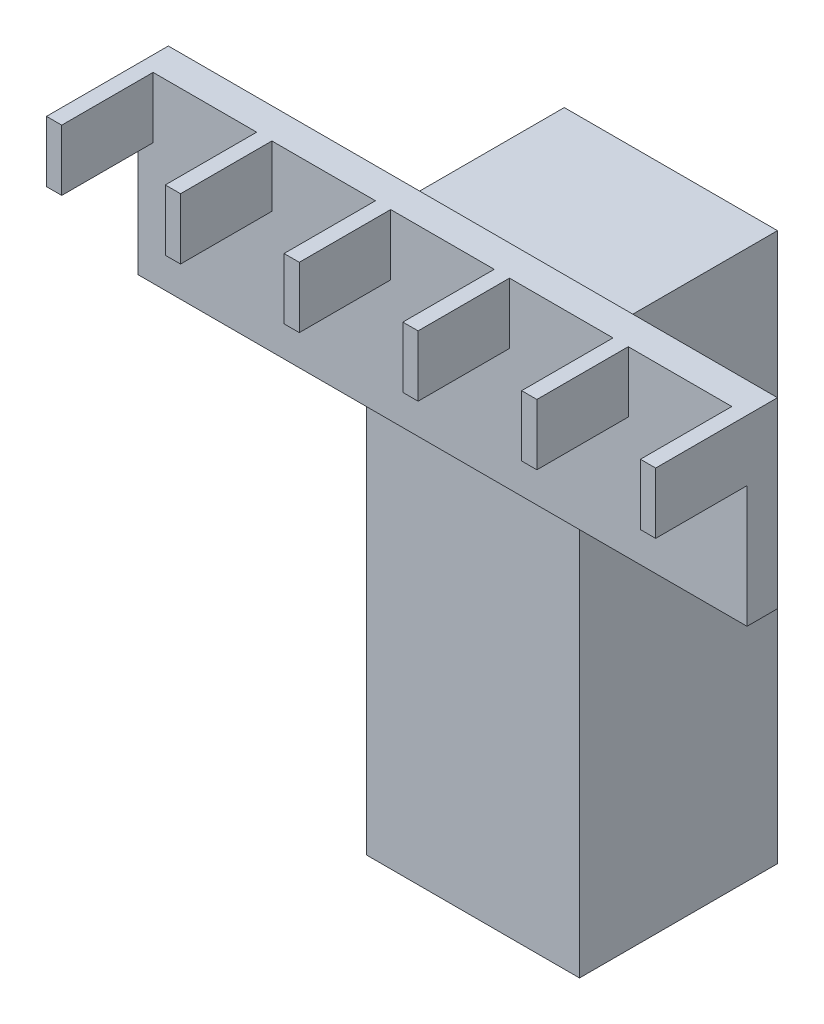
SolidWorks part; units mm, degrees
ref_plane "Front Plane" through (0, 0, 0) normal (0, 0, 1) x (1, 0, 0)
ref_plane "Top Plane" through (0, 0, 0) normal (0, 1, 0) x (1, 0, 0)
ref_plane "Right Plane" through (0, 0, 0) normal (1, 0, 0) x (0, 0, -1)
sketch "Sketch1" plane through (0, 0, 0) normal (0, 0, 1) x (1, 0, 0)
  line L1 (0, 0) -> (127, 0)
  line L2 (0, 0) -> (0, 38.1)
  line L3 (0, 38.1) -> (127, 38.1)
  line L4 (127, 0) -> (127, 38.1)
  dimension "D1" = 127
  dimension "D2" = 38.1
extrude "Boss-Extrude1" add sketch "Sketch1" along normal blind 6.35
sketch "Sketch2" plane through (0, 0, 6.35) normal (0, 0, 1) x (1, 0, 0)
  line L0 (24.765, 38.1) -> (27.94, 38.1)
  line L1 (0, 38.1) -> (3.175, 38.1)
  line L2 (0, 38.1) -> (0, 25.4)
  line L3 (0, 25.4) -> (3.175, 25.4)
  line L4 (3.175, 38.1) -> (3.175, 25.4)
  line L5 (24.765, 38.1) -> (24.765, 25.4)
  line L6 (24.765, 25.4) -> (27.94, 25.4)
  line L7 (27.94, 38.1) -> (27.94, 25.4)
  line L8 (49.53, 38.1) -> (52.705, 38.1)
  line L9 (49.53, 38.1) -> (49.53, 25.4)
  line L10 (49.53, 25.4) -> (52.705, 25.4)
  line L11 (52.705, 38.1) -> (52.705, 25.4)
  line L12 (74.295, 38.1) -> (77.47, 38.1)
  line L13 (74.295, 38.1) -> (74.295, 25.4)
  line L14 (74.295, 25.4) -> (77.47, 25.4)
  line L15 (77.47, 38.1) -> (77.47, 25.4)
  line L16 (99.06, 38.1) -> (102.235, 38.1)
  line L17 (99.06, 38.1) -> (99.06, 25.4)
  line L18 (99.06, 25.4) -> (102.235, 25.4)
  line L19 (102.235, 38.1) -> (102.235, 25.4)
  line L20 (123.825, 38.1) -> (127, 38.1)
  line L21 (123.825, 38.1) -> (123.825, 25.4)
  line L22 (123.825, 25.4) -> (127, 25.4)
  line L23 (127, 38.1) -> (127, 25.4)
  dimension "D1" = 12.7
  dimension "D2" = 3.175
  dimension "D3" = 6
extrude "Boss-Extrude2" add sketch "Sketch2" along normal blind 19.05
sketch "Sketch3" plane through (0, 0, 0) normal (0, 0, -1) x (-1, 0, 0)
  line L0 (0, 0) -> (-127, 0) construction
  line L1 (-41.275, 26.9875) -> (-85.725, 26.9875)
  line L2 (-41.275, 26.9875) -> (-41.275, -87.3125)
  line L4 (-85.725, 26.9875) -> (-85.725, -87.3125)
  line L5 (-41.275, 26.9875) -> (-63.5, 0) construction
  line L6 (-63.5, 0) -> (-85.725, 26.9875) construction
  line L7 (-85.725, -87.3125) -> (-41.275, -87.3125)
  point P0 (-63.5, 0)
  dimension "D1" = 44.45
  dimension "D2" = 26.9875
  dimension "D3" = 114.3
extrude "Boss-Extrude3" add sketch "Sketch3" along normal blind 41.275
sketch "Sketch4" plane through (0, -87.3125, 0) normal (0, -1, 0) x (1, 0, 0)
  line L0 (85.725, -41.275) -> (85.725, 0) construction
  line L1 (82.55, -3.175) -> (44.45, -3.175)
  line L2 (82.55, -3.175) -> (82.55, -38.1)
  line L3 (82.55, -38.1) -> (44.45, -38.1)
  line L4 (44.45, -3.175) -> (44.45, -38.1)
  line L5 (82.55, -3.175) -> (44.45, -38.1) construction
  line L6 (82.55, -38.1) -> (44.45, -3.175) construction
  line L7 (41.275, -41.275) -> (41.275, 0) construction
  line L8 (85.725, -41.275) -> (41.275, -41.275) construction
  point P0 (63.5, -20.6375)
  dimension "D1" = 3.175
  dimension "D2" = 3.175
  dimension "D3" = 3.175
  dimension "D4" = 34.925
extrude "Cut-Extrude1" cut sketch "Sketch4" against normal blind 50.8
sketch "Sketch5" plane through (0, 0, -41.275) normal (0, 0, -1) x (-1, 0, 0)
  line L0 (-85.725, 26.9875) -> (-85.725, -87.3125) construction
  line L2 (-41.275, 26.9875) -> (-85.725, 26.9875) construction
  circle A0 centre (-73.025, -49.2125) radius 6.35
  circle A1 centre (-53.975, -49.2125) radius 6.35
  dimension "D1" = 12.7
  dimension "D2" = 12.7
  dimension "D3" = 19.05
  dimension "D4" = 12.7
  dimension "D5" = 76.2
extrude "Cut-Extrude2" cut sketch "Sketch5" against normal blind 23.8125
